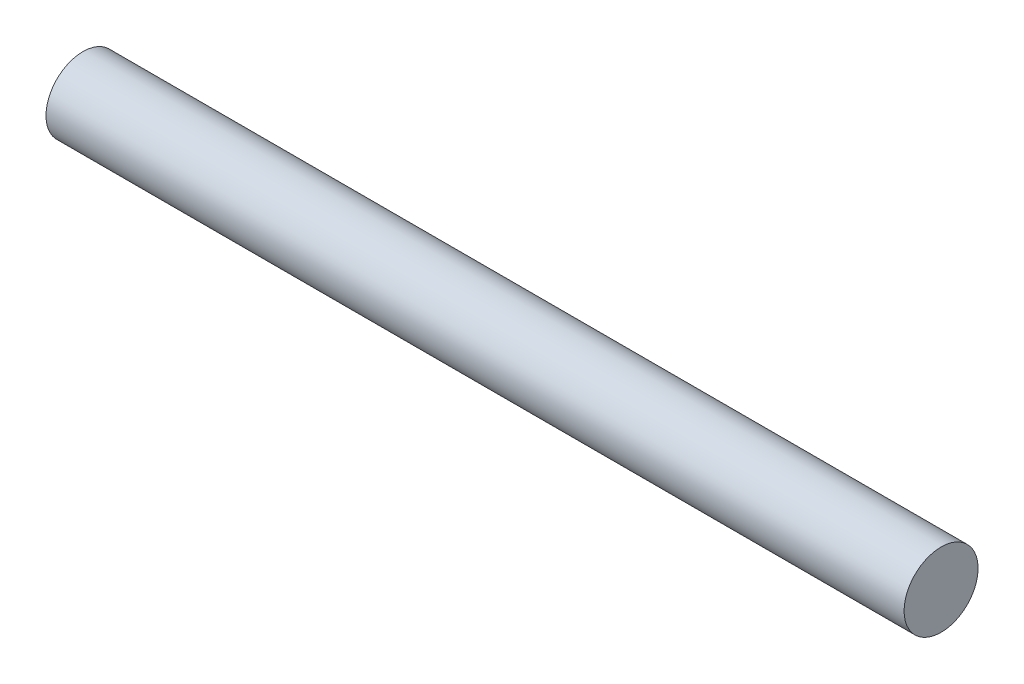
SolidWorks part; units mm, degrees
material "1023 Carbon Steel Sheet (SS)"
ref_plane "Front Plane" through (0, 0, 0) normal (0, 0, 1) x (1, 0, 0)
ref_plane "Top Plane" through (0, 0, 0) normal (0, 1, 0) x (1, 0, 0)
ref_plane "Right Plane" through (0, 0, 0) normal (1, 0, 0) x (0, 0, -1)
sketch "Sketch1" plane through (0, 0, 0) normal (1, 0, 0) x (0, 0, -1)
  circle A0 centre (0, 0) radius 2.5
  dimension "D1" = 5
extrude "Boss-Extrude1" add sketch "Sketch1" along normal blind 58
